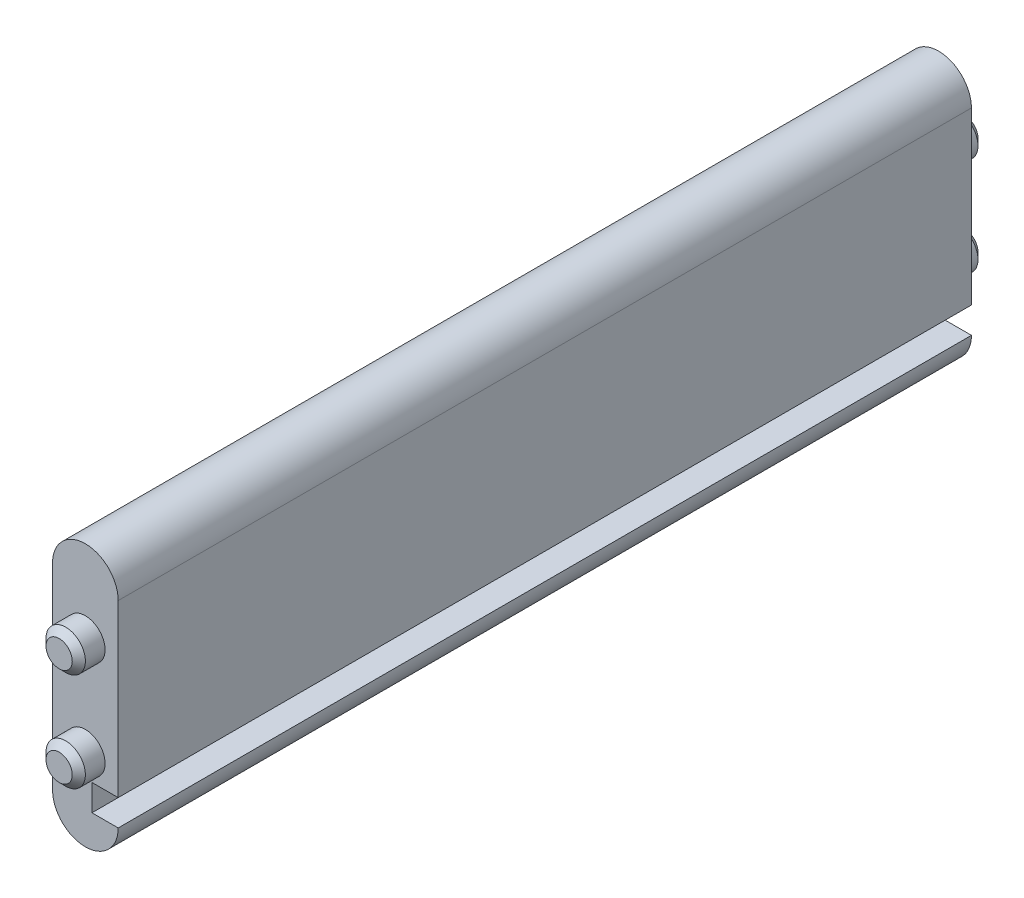
SolidWorks part; units mm, degrees
ref_plane "前基準面" through (0, 0, 0) normal (0, 0, 1) x (1, 0, 0)
ref_plane "上基準面" through (0, 0, 0) normal (0, 1, 0) x (1, 0, 0)
ref_plane "右基準面" through (0, 0, 0) normal (1, 0, 0) x (0, 0, -1)
sketch "草圖1" plane through (0, 0, 0) normal (0, 0, 1) x (1, 0, 0)
  line L0 (0, 15) -> (0, -15) construction
  line L1 (-5, 15) -> (-5, -15)
  line L2 (5, 15) -> (5, -11)
  line L3 (5, 15) -> (5, -15) construction
  line L4 (5, -15) -> (1, -15)
  line L6 (5, -11) -> (1, -11)
  line L7 (1, -15) -> (1, -11)
  arc A0 (-5, 15) -> (5, 15) centre (0, 15) cw
  arc A1 (-5, -15) -> (5, -15) centre (0, -15) ccw
  dimension "D2" = 40
  dimension "D1" = 10
  dimension "D3" = 4
  dimension "D4" = 4
extrude "伸長1" add sketch "草圖1" along normal mid plane 130
sketch "草圖2" plane through (0, 0, 65) normal (0, 0, 1) x (1, 0, 0)
  line L0 (0, 7.5) -> (0, 0) construction
  line L1 (0, 0) -> (8.2615, 0) construction
  circle A0 centre (0, 7.5) radius 3
  circle A1 centre (0, -7.5) radius 3
  dimension "D1" = 6
  dimension "D2" = 15
extrude "伸長2" add sketch "草圖2" along normal blind 4
chamfer "導角1" distance 1 angle 45 2 edges at (-3, -7.5, 69) (3, 7.5, 69)
mirror "鏡射1" about plane through (0, 0, 0) normal (0, 0, 1) of "導角1", "伸長2"
